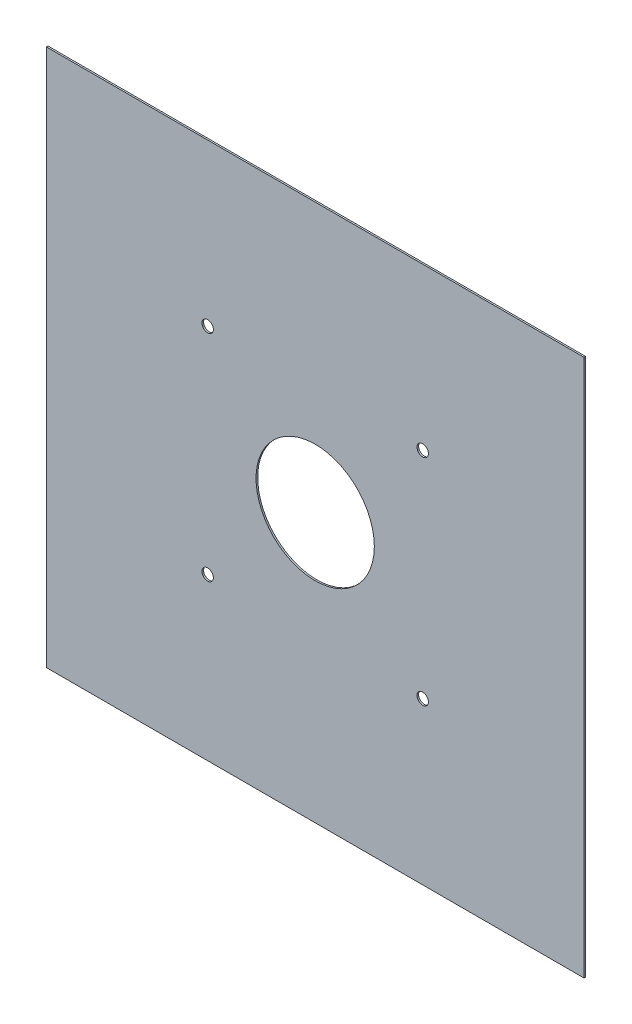
SolidWorks part; units mm, degrees
ref_plane "Front Plane" through (0, 0, 0) normal (0, 0, 1) x (1, 0, 0)
ref_plane "Top Plane" through (0, 0, 0) normal (0, 1, 0) x (1, 0, 0)
ref_plane "Right Plane" through (0, 0, 0) normal (1, 0, 0) x (0, 0, -1)
sketch "Sketch1" plane through (0, 0, 0) normal (0, 0, 1) x (1, 0, 0)
  line L1 (12.7, 374.6) -> (-387.3, 374.6)
  line L2 (12.7, 374.6) -> (12.7, -25.4)
  line L3 (12.7, -25.4) -> (-387.3, -25.4)
  line L4 (-387.3, 374.6) -> (-387.3, -25.4)
extrude "Boss-Extrude1" add sketch "Sketch1" along normal blind 1.2
sketch "Sketch2" plane through (0, 0, 1.2) normal (0, 0, 1) x (1, 0, 0)
  line L0 (-187.3, 374.6) -> (-187.3, -25.4) construction
  line L1 (12.7, 374.6) -> (-387.3, 374.6) construction
  line L2 (-387.3, -25.4) -> (12.7, -25.4) construction
  line L4 (-267.3, 254.6) -> (-107.3, 254.6) construction
  line L5 (-267.3, 254.6) -> (-267.3, 94.6) construction
  line L6 (-267.3, 94.6) -> (-107.3, 94.6) construction
  line L7 (-107.3, 254.6) -> (-107.3, 94.6) construction
  line L8 (-267.3, 254.6) -> (-107.3, 94.6) construction
  line L9 (-267.3, 94.6) -> (-107.3, 254.6) construction
  circle A0 centre (-187.3, 174.6) radius 44
  circle A1 centre (-267.3, 254.6) radius 4.25
  circle A2 centre (-267.3, 94.6) radius 4.25
  circle A3 centre (-107.3, 94.6) radius 4.25
  circle A4 centre (-107.3, 254.6) radius 4.25
  dimension "D2" = 88
  dimension "D3" = 8.5
  dimension "D1" = 160
extrude "Cut-Extrude1" cut sketch "Sketch2" against normal through all
